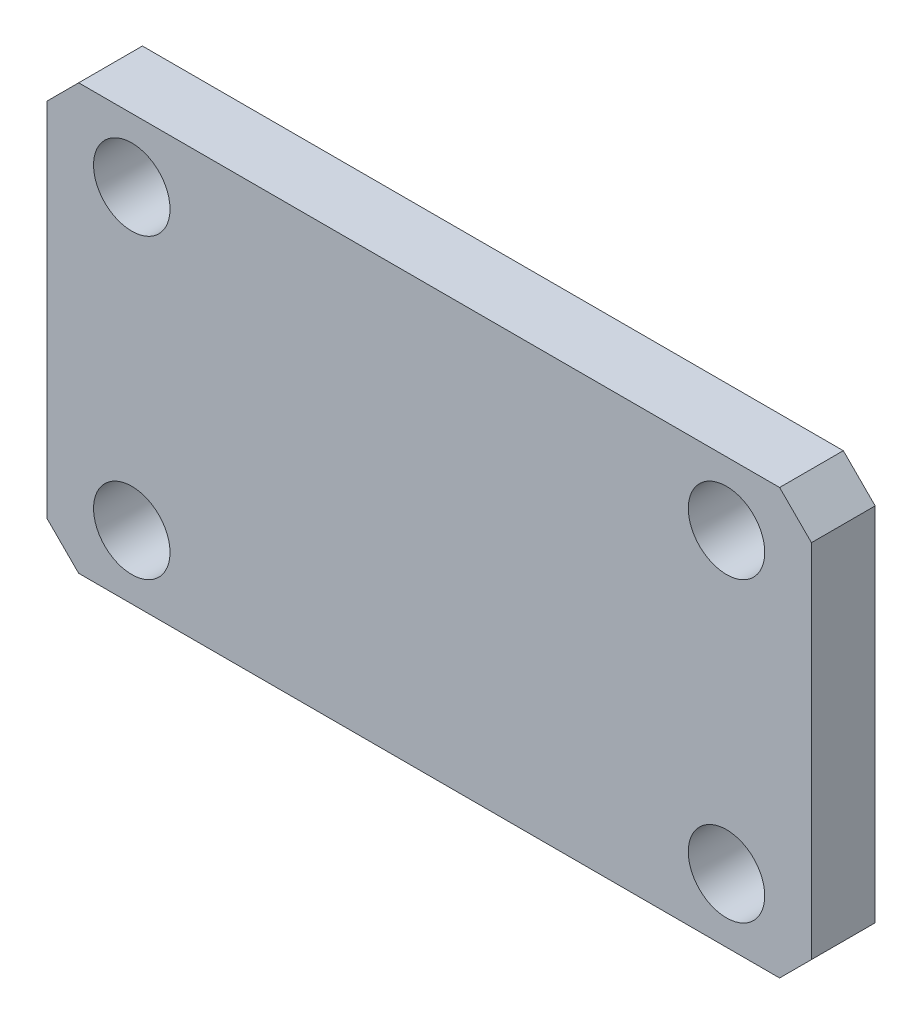
SolidWorks part; units mm, degrees
material "PETG"
ref_plane "Płaszczyzna przednia" through (0, 0, 0) normal (0, 0, 1) x (1, 0, 0)
ref_plane "Płaszczyzna górna" through (0, 0, 0) normal (0, 1, 0) x (1, 0, 0)
ref_plane "Płaszczyzna prawa" through (0, 0, 0) normal (1, 0, 0) x (0, 0, -1)
sketch "Sketch1" plane through (0, 0, 0) normal (0, 0, 1) x (1, 0, 0)
  line L1 (0, 0) -> (36, 0)
  line L2 (0, 0) -> (0, 20)
  line L3 (0, 20) -> (36, 20)
  line L4 (36, 0) -> (36, 20)
  dimension "D1" = 20
  dimension "D2" = 36
extrude "Boss-Extrude1" add sketch "Sketch1" along normal blind 3
hole_wizard "M3 Clearance Hole1" positions "Sketch2" profile "Sketch3" hole size "M3" standard "DIN"
sketch "Sketch2" plane through (0, 0, 3) normal (0, 0, 1) x (1, 0, 0)
  line L0 (4, 3) -> (32, 17) construction
  line L2 (32, 3) -> (4, 17) construction
  line L4 (18, 10) -> (18, 0) construction
  line L5 (0, 0) -> (36, 0) construction
  line L7 (18, 10) -> (36, 10) construction
  line L8 (36, 0) -> (36, 20) construction
  point P0 (4, 17)
  point P6 (32, 17)
  point P7 (32, 3)
  point P8 (4, 3)
  dimension "D3" = 14
  dimension "D4" = 28
  dimension "D1" = 2
  dimension "D2" = 2
sketch "Sketch3" plane through (4, 17, 3) normal (1, 0, 0) x (0, -1, 0)
  line L0 (0, 0) -> (0, 11.0815)
  line L1 (0, 11.0815) -> (1.8, 10)
  line L2 (1.8, 10) -> (1.8, 0)
  line L5 (1.8, 0) -> (0, 0)
  line L10 (0, 11.0815) -> (-1.8, 10) construction
  line L11 (0, -6.35) -> (0, 107.95) construction
  dimension "Hole Dia." = 3.6
  dimension "Hole Depth" = 10
  dimension "Drill Angle" = 118
chamfer "Chamfer1" distance 1.5 angle 45 4 edges at (36, 20, 1.5) (36, 0, 1.5) (0, 0, 1.5) (0, 20, 1.5)
sketch "Sketch4" plane through (0, 0, 0) normal (0, 0, 1) x (1, 0, 0)
  line L0 (18, 20) -> (18, 16) construction
  line L1 (8, 16) -> (28, 16)
  line L2 (8, 16) -> (8, 4)
  line L3 (8, 4) -> (28, 4)
  line L4 (28, 16) -> (28, 4)
  line L5 (34.5, 20) -> (1.5, 20) construction
  line L6 (28, 10) -> (36, 10) construction
  line L7 (36, 1.5) -> (36, 18.5) construction
  dimension "D1" = 12
  dimension "D2" = 20
extrude "Cut-Extrude1" cut sketch "Sketch4" along normal blind 0.5
sketch "Sketch5" plane through (0, 0, 0.5) normal (0, 0, -1) x (-1, 0, 0)
  line L12 (-9, 5) -> (-9, 15)
  line L13 (-9, 15) -> (-27, 15)
  line L14 (-27, 15) -> (-27, 5)
  line L15 (-27, 5) -> (-9, 5)
  line L16 (-8, 4) -> (-8, 16)
  line L17 (-8, 16) -> (-28, 16)
  line L18 (-28, 16) -> (-28, 4)
  line L19 (-28, 4) -> (-8, 4)
  line L20 (-8, 4) -> (-8, 16)
  line L21 (-8, 16) -> (-28, 16)
  line L22 (-28, 16) -> (-28, 4)
  line L23 (-28, 4) -> (-8, 4)
  dimension "D1" = 0
  dimension "D2" = 1
extrude "Boss-Extrude2" add sketch "Sketch5" along normal blind 1 separate body contours L14 L15 L12 L13
